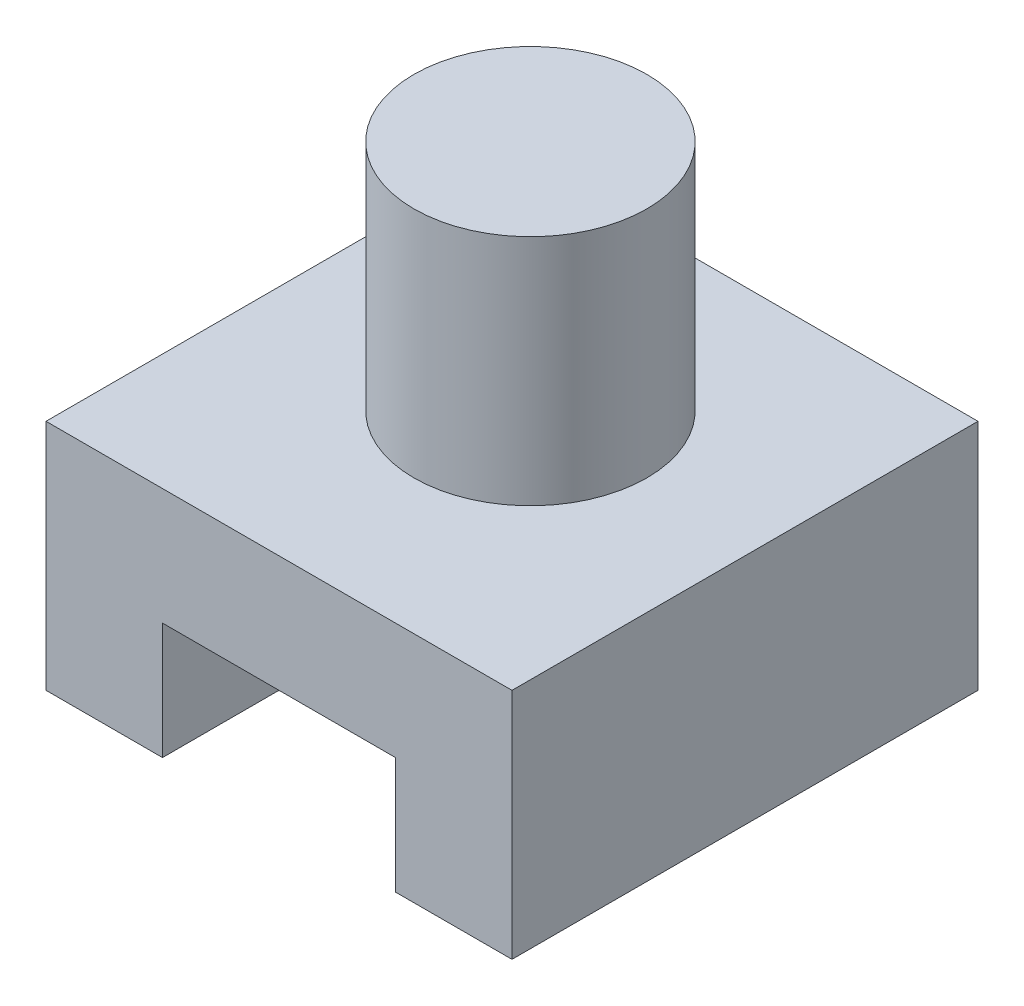
SolidWorks part; units mm, degrees
ref_plane "Front Plane" through (0, 0, 0) normal (0, 0, 1) x (1, 0, 0)
ref_plane "Top Plane" through (0, 0, 0) normal (0, 1, 0) x (1, 0, 0)
ref_plane "Right Plane" through (0, 0, 0) normal (1, 0, 0) x (0, 0, -1)
sketch "Sketch2" plane through (0, 0, 0) normal (0, 1, 0) x (1, 0, 0)
  line L0 (0, 0) -> (40, 0)
  line L1 (40, 0) -> (40, 40)
  line L2 (40, 40) -> (0, 40)
  line L3 (0, 40) -> (0, 0)
  dimension "D1" = 40
  dimension "D2" = 40
extrude "Boss-Extrude1" add sketch "Sketch2" along normal blind 20
sketch "Sketch3" plane through (0, 0, 0) normal (0, 0, 1) x (1, 0, 0)
  line L0 (10, 0) -> (10, 10)
  line L1 (0, 0) -> (40, 0) construction
  line L2 (10, 10) -> (30, 10)
  line L3 (30, 10) -> (30, 0)
  line L4 (30, 0) -> (10, 0)
  line L5 (40, 20) -> (40, 0) construction
  line L6 (0, 20) -> (0, 0) construction
  line L7 (0, 20) -> (40, 20) construction
  dimension "D1" = 10
  dimension "D2" = 10
  dimension "D3" = 10
extrude "Cut-Extrude1" cut sketch "Sketch3" against normal blind 20
sketch "Sketch6" plane through (0, 20, 0) normal (0, 1, 0) x (1, 0, 0)
  line L0 (20, 45.2409) -> (20, -2.0822) construction
  line L1 (40, 0) -> (40, 40) construction
  circle A0 centre (20, 21.5794) radius 10
  point P3 (20, 21.5794)
  dimension "D2" = 20
  dimension "D1" = 20
extrude "Boss-Extrude2" add sketch "Sketch6" along normal blind 20
